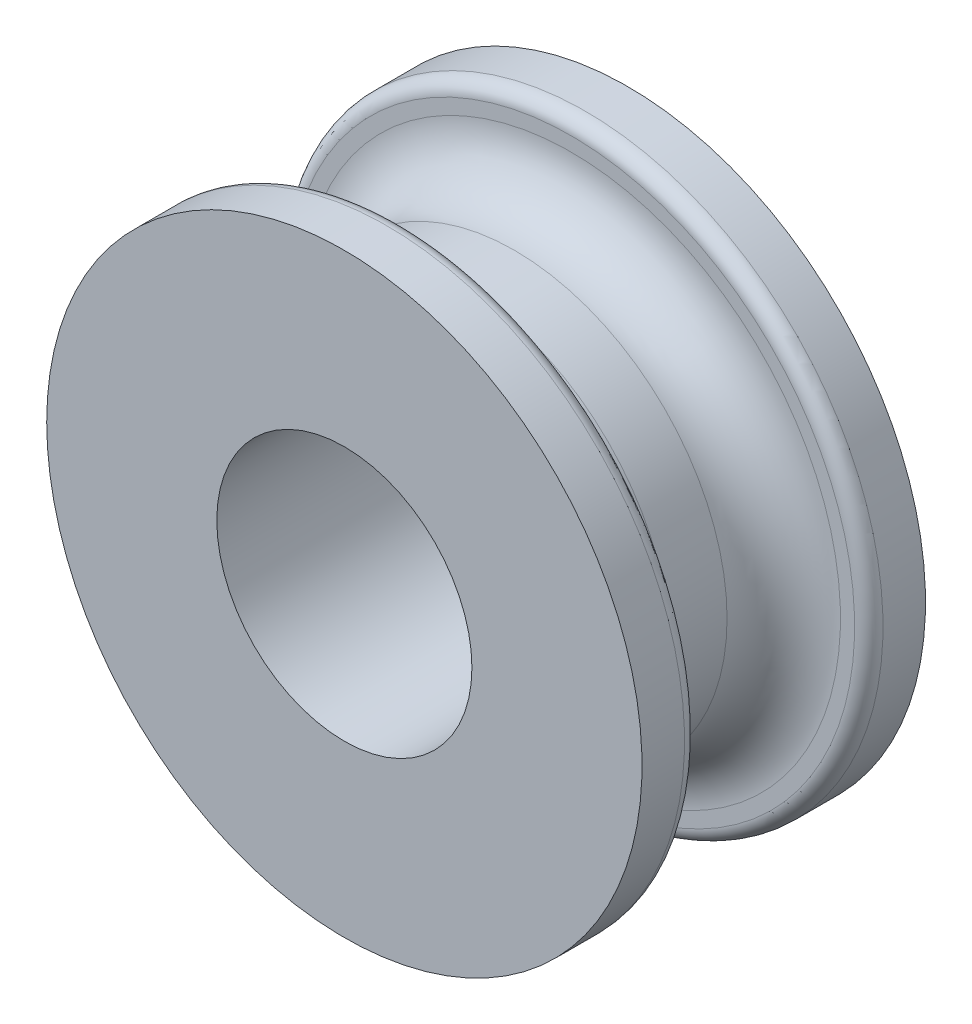
SolidWorks part; units mm, degrees
ref_plane "Front Plane" through (0, 0, 0) normal (0, 0, 1) x (1, 0, 0)
ref_plane "Top Plane" through (0, 0, 0) normal (0, 1, 0) x (1, 0, 0)
ref_plane "Right Plane" through (0, 0, 0) normal (1, 0, 0) x (0, 0, -1)
sketch "Sketch2" plane through (0, 0, 0) normal (0, 1, 0) x (1, 0, 0)
  line L0 (4.5, 0) -> (10.5, 0)
  line L1 (-55, 0) -> (55, 0) construction
  line L2 (10.5, 0) -> (10.5, 1.5)
  line L3 (10, 2) -> (9.5, 2)
  line L4 (7.5, 4) -> (7.5, 6)
  line L5 (9.5, 8) -> (10, 8)
  line L6 (10.5, 8.5) -> (10.5, 10)
  line L7 (10.5, 10) -> (4.5, 10)
  line L8 (4.5, 10) -> (4.5, 0)
  line L9 (0, -55) -> (0, 55) construction
  line L10 (7.5, 5) -> (4.5, 5) construction
  line L11 (4.5, 10) -> (0, 10) construction
  line L12 (0, 10) -> (0, 0) construction
  line L13 (0, 0) -> (4.5, 0) construction
  arc A0 (9.5, 2) -> (7.5, 4) centre (9.5, 4) cw
  arc A1 (7.5, 6) -> (9.5, 8) centre (9.5, 6) cw
  arc A2 (10.5, 1.5) -> (10, 2) centre (10, 1.5) ccw
  arc A3 (10.5, 8.5) -> (10, 8) centre (10, 8.5) cw
  point P20 (7.5, 8)
  point P25 (10.5, 8)
  dimension "D5" = 2
  dimension "D6" = 0.5
  dimension "D1" = 7.5
  dimension "D2" = 3
  dimension "D3" = 3
  dimension "D4" = 10
  dimension "D7" = 2
revolve "Revolve1" add sketch "Sketch2" angle 360 about L12
